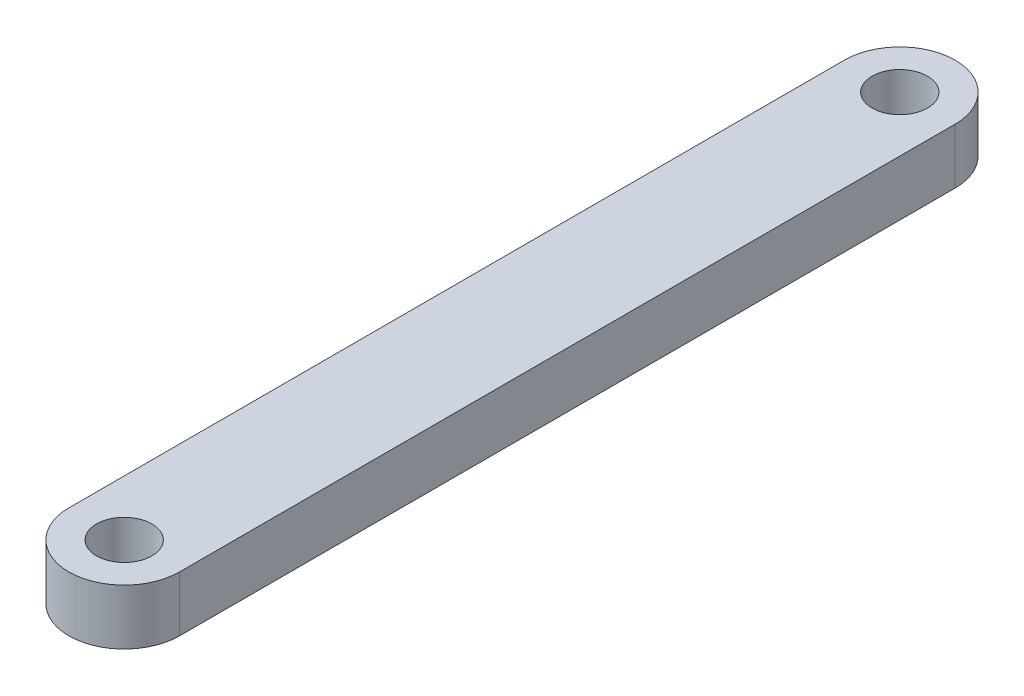
SolidWorks part; units mm, degrees
material "Aleación 1060"
ref_plane "Alzado" through (0, 0, 0) normal (0, 0, 1) x (1, 0, 0)
ref_plane "Planta" through (0, 0, 0) normal (0, 1, 0) x (1, 0, 0)
ref_plane "Vista lateral" through (0, 0, 0) normal (1, 0, 0) x (0, 0, -1)
sketch "Croquis1" plane through (0, 0, 0) normal (0, 1, 0) x (1, 0, 0)
  line L0 (0, 0) -> (0, 70) construction
  line L1 (-5, 70) -> (-5, 0)
  line L2 (5, 70) -> (5, 0)
  circle A0 centre (0, 0) radius 2.5
  circle A1 centre (0, 70) radius 2.5
  arc A2 (5, 70) -> (-5, 70) centre (0, 70) ccw
  arc A3 (-5, 0) -> (5, 0) centre (0, 0) ccw
  dimension "D1" = 5
  dimension "D3" = 5
  dimension "D4" = 10
  dimension "D5" = 10
  dimension "D2" = 70
extrude "Saliente-Extruir1" add sketch "Croquis1" along normal blind 5
